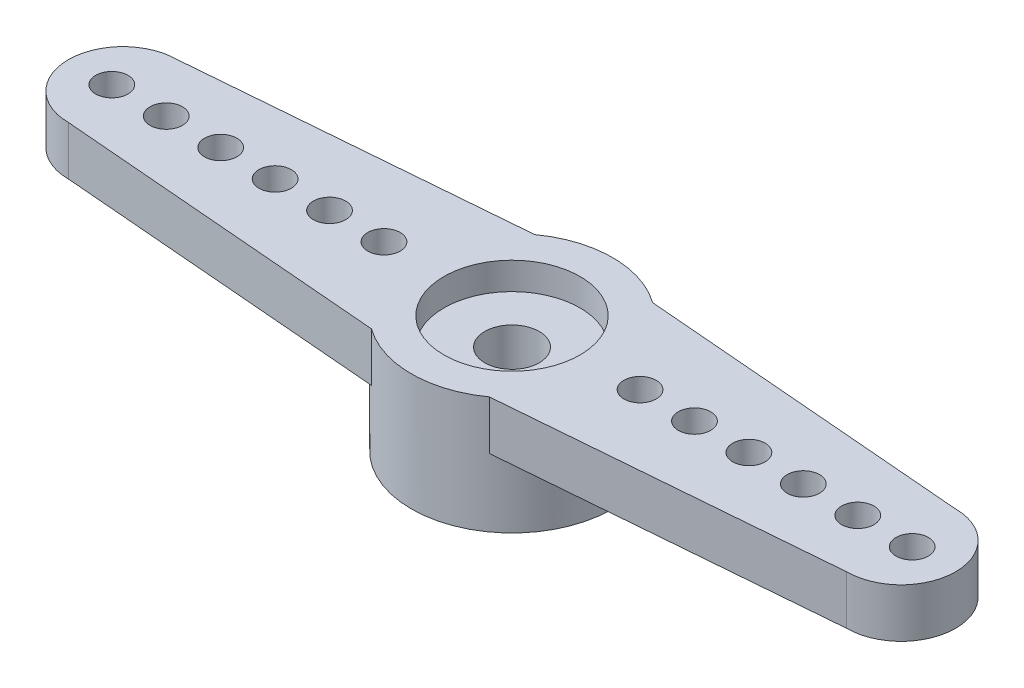
SolidWorks part; units mm, degrees
ref_plane "Alzado" through (0, 0, 0) normal (0, 0, 1) x (1, 0, 0)
ref_plane "Planta" through (0, 0, 0) normal (0, 1, 0) x (1, 0, 0)
ref_plane "Vista lateral" through (0, 0, 0) normal (1, 0, 0) x (0, 0, -1)
sketch "Croquis1" plane through (0, 0, 0) normal (0, 1, 0) x (1, 0, 0)
  circle A0 centre (0, 0) radius 3.7
  dimension "D1" = 7.4
extrude "Saliente-Extruir2" add sketch "Croquis1" along normal blind 4.3 contours A0
sketch "Croquis2" plane through (0, 0, 0) normal (0, -1, 0) x (1, 0, 0)
  circle A0 centre (0, 0) radius 2.5
  dimension "D1" = 5
extrude "Cortar-Extruir1" cut sketch "Croquis2" against normal blind 1.5
sketch "Croquis3" plane through (0, 4.3, 0) normal (0, 1, 0) x (1, 0, 0)
  circle A0 centre (0, 0) radius 2.5
  dimension "D1" = 5
extrude "Cortar-Extruir2" cut sketch "Croquis3" against normal blind 1
sketch "Croquis4" plane through (0, 3.3, 0) normal (0, 1, 0) x (1, 0, 0)
  circle A0 centre (0, 0) radius 1
  dimension "D1" = 2
extrude "Cortar-Extruir3" cut sketch "Croquis4" against normal blind 1.8
sketch "Croquis5" plane through (0, 4.3, 0) normal (0, 1, 0) x (1, 0, 0)
  line L0 (0, 0) -> (-2.1656, 0) construction
  line L1 (-2.1656, 3) -> (-3.1202, 0)
  line L2 (-3.1202, 0) -> (-2.1656, -3)
  line L3 (-2.1656, 0) -> (-2.5, 0) construction
  line L4 (-3.7, 0) -> (-16.3, 0) construction
  line L5 (-14.3, 0) -> (-14.3, 2) construction
  line L6 (-14.3, 0) -> (-14.3, -2) construction
  line L7 (-2.1656, 3) -> (-14.3, 2)
  line L8 (-2.1656, -3) -> (-14.3, -2)
  line L9 (0, 5.1944) -> (0, -4.3435) construction
  line L10 (3.1202, 0) -> (2.1656, -3)
  line L11 (2.1656, -3) -> (14.3, -2)
  line L12 (2.1656, 3) -> (14.3, 2)
  line L13 (2.1656, 3) -> (3.1202, 0)
  arc A0 (-14.3, 2) -> (-14.3, -2) centre (-14.3, 0) ccw
  arc A1 (14.3, 2) -> (14.3, -2) centre (14.3, 0) cw
  circle A3 centre (0, 0) radius 3.7 construction
  circle A4 centre (0, 0) radius 2.5 construction
  point P2 (-14.3, 0)
  dimension "D1" = 2.1656
  dimension "D2" = 12.6
  dimension "D3" = 2
  dimension "D4" = 2
  dimension "D5" = 2
extrude "Saliente-Extruir3" add sketch "Croquis5" against normal blind 1.8
sketch "Croquis6" plane through (0, 4.3, 0) normal (0, 1, 0) x (1, 0, 0)
  line L0 (0, 0) -> (-16.3, 0) construction
  line L1 (2, 0) -> (-14.3, 0) construction
  line L2 (4, 0) -> (-12.3, 0) construction
  line L3 (6, 0) -> (-10.3, 0) construction
  line L4 (8, 0) -> (-8.3, 0) construction
  line L5 (10, 0) -> (-6.3, 0) construction
  line L6 (0, 5.4913) -> (0, -4.5375) construction
  arc A0 (-14.3, 2) -> (-14.3, -2) centre (-14.3, 0) ccw construction
  circle A1 centre (-14.705, 0) radius 0.595
  circle A2 centre (-12.705, 0) radius 0.595
  circle A3 centre (-10.705, 0) radius 0.595
  circle A4 centre (-8.705, 0) radius 0.595
  circle A5 centre (-6.705, 0) radius 0.595
  circle A6 centre (-4.705, 0) radius 0.595
  circle A7 centre (14.705, 0) radius 0.595
  circle A8 centre (12.705, 0) radius 0.595
  circle A9 centre (10.705, 0) radius 0.595
  circle A10 centre (8.705, 0) radius 0.595
  circle A11 centre (6.705, 0) radius 0.595
  circle A12 centre (4.705, 0) radius 0.595
  point P6 (-14.705, 0)
  dimension "D2" = 1.19
  dimension "D1" = 1.595
  dimension "D4" = 21.41
  dimension "D3" = 6
extrude "Cortar-Extruir4" cut sketch "Croquis6" against normal blind 1.8
